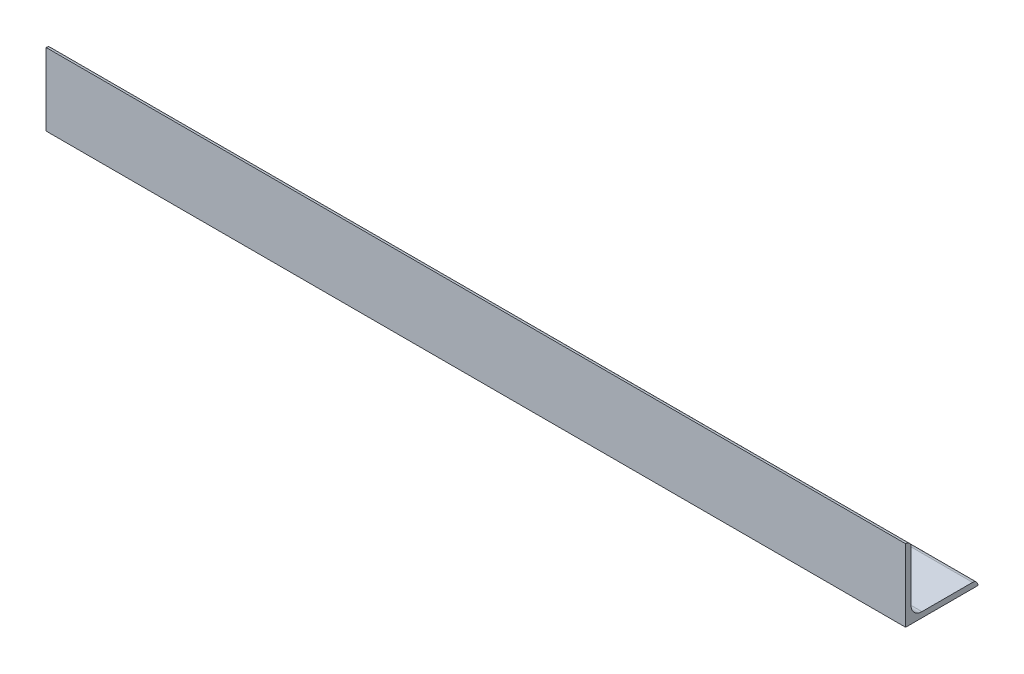
SolidWorks part; units mm, degrees
ref_plane "Front Plane" through (0, 0, 0) normal (0, 0, 1) x (1, 0, 0)
ref_plane "Top Plane" through (0, 0, 0) normal (0, 1, 0) x (1, 0, 0)
ref_plane "Right Plane" through (0, 0, 0) normal (1, 0, 0) x (0, 0, -1)
sketch "Sketch1" plane through (0, 0, 0) normal (0, 1, 0) x (1, 0, 0)
  line L0 (0, 0) -> (475, 0)
  dimension "D1" = 475
other "L angle (equal) 40X40X3(9)"
ref_plane "Plane1" through (0, 0, 0) normal (1, 0, 0) x (0, 0, -1)
sketch "Sketch13" plane through (0, 0, 0) normal (1, 0, 0) x (0, 0, -1)
  line L0 (0, 40) -> (0, 0)
  line L2 (3, 37) -> (3, 9)
  line L3 (9, 3) -> (37, 3)
  line L5 (40, 0) -> (0, 0)
  arc A0 (3, 37) -> (0, 40) centre (0, 37) ccw
  arc A1 (40, 0) -> (37, 3) centre (37, 0) ccw
  arc A2 (9, 3) -> (3, 9) centre (9, 9) cw
  point P8 (0, 20)
  point P9 (20, 0)
  point P10 (0, 0)
  dimension "Radius_2" = 3
  dimension "Radius_1" = 6
  dimension "V_leg" = 40
  dimension "H_leg" = 40
  dimension "thickness" = 3
